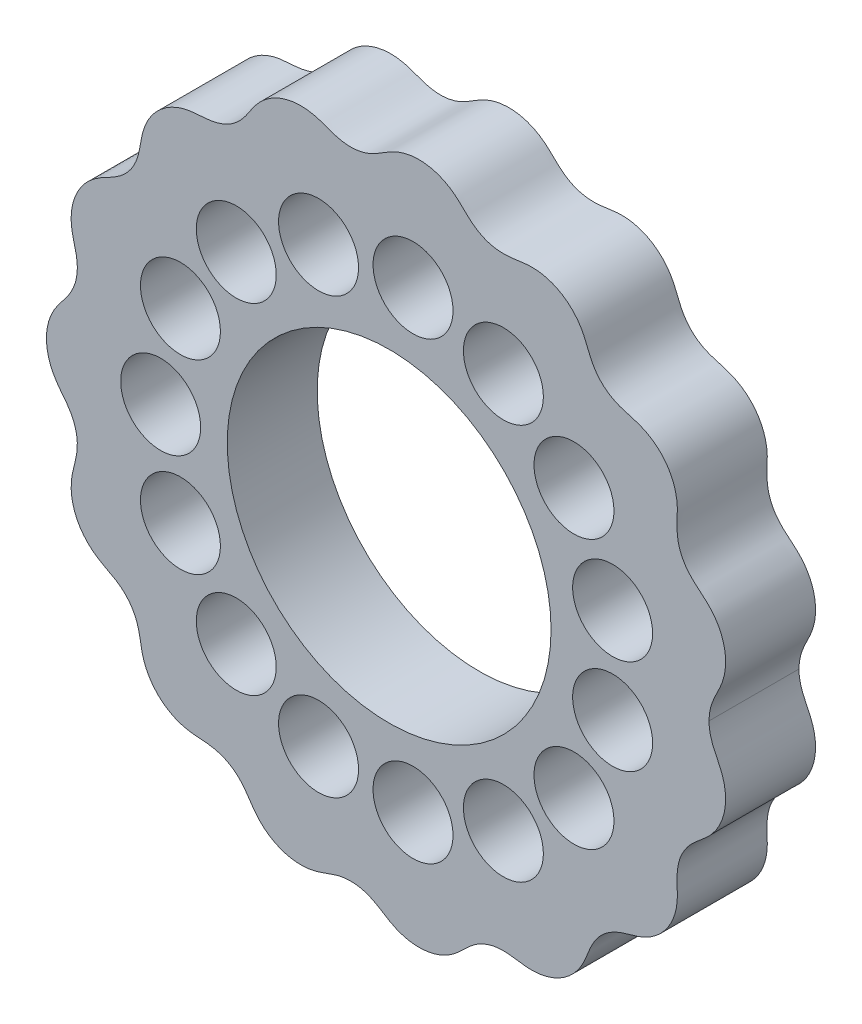
SolidWorks part; units mm, degrees
material "ABS"
ref_plane "Front Plane" through (0, 0, 0) normal (0, 0, 1) x (1, 0, 0)
ref_plane "Top Plane" through (0, 0, 0) normal (0, 1, 0) x (1, 0, 0)
ref_plane "Right Plane" through (0, 0, 0) normal (1, 0, 0) x (0, 0, -1)
sketch "Sketch2" plane through (0, 0, 0) normal (0, 0, 1) x (1, 0, 0)
  line L0 (0, 0) -> (18.3781, 0) construction
  line L1 (0, 0) -> (-12.7, 0) construction
  line L6 (0, 0) -> (-26.7529, 0) construction
  circle A0 centre (0, 0) radius 9
  circle A1 centre (-12.7, 0) radius 2.2225
  circle A10 centre (-11.602, 5.1656) radius 2.2225
  circle A11 centre (-8.498, 9.4379) radius 2.2225
  circle A12 centre (-3.9245, 12.0784) radius 2.2225
  circle A13 centre (1.3275, 12.6304) radius 2.2225
  circle A14 centre (6.35, 10.9985) radius 2.2225
  circle A15 centre (10.2745, 7.4649) radius 2.2225
  circle A16 centre (12.4225, 2.6405) radius 2.2225
  circle A17 centre (12.4225, -2.6405) radius 2.2225
  circle A18 centre (10.2745, -7.4649) radius 2.2225
  circle A19 centre (6.35, -10.9985) radius 2.2225
  circle A20 centre (1.3275, -12.6304) radius 2.2225
  circle A21 centre (-3.9245, -12.0784) radius 2.2225
  circle A22 centre (-8.498, -9.4379) radius 2.2225
  circle A23 centre (-11.602, -5.1656) radius 2.2225
  spline S0 degree 4 poles (17.78, 0) (17.78, 0.0244) (17.7807, 0.067) (17.7836, 0.1435) (17.7924, 0.267) (17.8127, 0.4353) (17.858, 0.6662) (17.9448, 0.9544) (18.081, 1.2802) (18.243, 1.6063) (18.4518, 2.028) (18.6305, 2.5252) (18.7221, 3.0926) (18.6984, 3.6926) (18.5877, 4.2118) (18.3912, 4.7145) (18.1084, 5.1856) (17.7679, 5.5735) (17.4029, 5.8854) (17.008, 6.2075) (16.5682, 6.6286) (16.2327, 7.1481) (16.0524, 7.7356) (16.0001, 8.251) (15.9991, 8.6116) (16.0206, 9.0306) (16.0292, 9.5107) (15.9471, 10.1461) (15.6638, 10.8967) (15.1871, 11.5476) (14.5569, 12.0443) (13.9761, 12.3143) (13.5161, 12.452) (13.1111, 12.5616) (12.7691, 12.6758) (12.2967, 12.8885) (11.871, 13.1931) (11.5254, 13.5862) (11.2662, 14.0347) (11.1178, 14.3634) (10.9667, 14.7548) (10.7805, 15.1975) (10.4492, 15.7456) (9.9577, 16.2466) (9.3671, 16.6208) (8.7488, 16.8381) (8.2396, 16.9232) (7.7623, 16.9292) (7.3264, 16.8812) (6.8495, 16.8026) (6.3206, 16.7557) (5.7346, 16.8115) (5.1268, 17.0239) (4.6337, 17.3466) (4.246, 17.7093) (3.9151, 18.0408) (3.6067, 18.3071) (3.1184, 18.6387) (2.4323, 18.9214) (1.6414, 19.0195) (0.8132, 18.8837) (0.2219, 18.6371) (-0.1896, 18.3896) (-0.5417, 18.1614) (-0.8545, 17.9819) (-1.327, 17.7696) (-1.9259, 17.632) (-2.5436, 17.6628) (-3.1282, 17.833) (-3.6046, 18.0141) (-4.0571, 18.1742) (-4.6853, 18.2995) (-5.492, 18.271) (-6.2641, 18.0249) (-6.9363, 17.5833) (-7.3777, 17.1156) (-7.6524, 16.7235) (-7.8817, 16.371) (-8.0964, 16.0772) (-8.4472, 15.686) (-8.8732, 15.3689) (-9.3609, 15.1585) (-9.8751, 15.0503) (-10.2369, 15.0113) (-10.6568, 14.9889) (-11.1337, 14.9471) (-11.7594, 14.7987) (-12.478, 14.4373) (-13.0772, 13.8918) (-13.5052, 13.2073) (-13.7107, 12.6007) (-13.7984, 12.1286) (-13.8654, 11.7146) (-13.9442, 11.3624) (-14.1083, 10.8715) (-14.3688, 10.4167) (-14.7255, 10.0347) (-15.2185, 9.6772) (-15.6699, 9.439) (-16.1793, 9.1821) (-16.7602, 8.7371) (-17.2688, 8.1172) (-17.5941, 7.3784) (-17.7091, 6.5847) (-17.6525, 5.9464) (-17.5418, 5.4793) (-17.4111, 4.9868) (-17.3233, 4.5098) (-17.321, 3.9878) (-17.4303, 3.4791) (-17.5906, 3.0811) (-17.7875, 2.7393) (-17.998, 2.4467) (-18.2143, 2.1781) (-18.4158, 1.9169) (-18.5901, 1.6545) (-18.7342, 1.3913) (-18.8479, 1.128) (-18.9239, 0.8973) (-18.9725, 0.705) (-19.0024, 0.553) (-19.0216, 0.4311) (-19.0342, 0.3261) (-19.042, 0.2308) (-19.0474, 0.131) (-19.0494, 0.0653) (-19.05, 0.0261) (-19.05, 0) knots 0.076308 0.076308 0.076308 0.076308 0.076308 0.077887 0.079057 0.080226 0.082566 0.087244 0.091922 0.0966 0.101861 0.107122 0.117645 0.12533 0.133015 0.139766 0.146517 0.154702 0.162887 0.167804 0.172722 0.182557 0.196068 0.200986 0.205904 0.210822 0.21574 0.223925 0.23211 0.245612 0.259114 0.267299 0.275484 0.280401 0.285319 0.290237 0.295154 0.308665 0.313583 0.318501 0.323419 0.328337 0.336522 0.344707 0.358209 0.366269 0.37433 0.380311 0.386291 0.392272 0.398253 0.406737 0.415222 0.424152 0.433082 0.438638 0.444195 0.449751 0.455308 0.470806 0.484308 0.492493 0.500678 0.505596 0.510514 0.515432 0.52035 0.533861 0.543696 0.548613 0.553531 0.561716 0.5699 0.583403 0.597169 0.605269 0.613369 0.618332 0.623295 0.628258 0.633221 0.646999 0.651962 0.656925 0.661888 0.666852 0.674952 0.683052 0.696818 0.71032 0.718505 0.726689 0.731607 0.736524 0.741442 0.746359 0.759871 0.764789 0.769707 0.779543 0.787728 0.795913 0.809415 0.822917 0.831101 0.839286 0.844204 0.849122 0.858957 0.865712 0.872468 0.877386 0.882304 0.887222 0.89214 0.896232 0.900324 0.904417 0.908509 0.911885 0.913573 0.91526 0.916948 0.918636 0.91948 0.920324 0.922011 0.922011 0.922011 0.922011 0.922011
  spline S2 degree 4 poles (18.0179, 5.2689) (18.0967, 5.1695) (18.2438, 4.9626) (18.4281, 4.6332) (18.6002, 4.1637) (18.6964, 3.6778) (18.7168, 3.1875) (18.6633, 2.7196) (18.5471, 2.2841) (18.4034, 1.9335) (18.2685, 1.6576) (18.1548, 1.4282) (18.0675, 1.2429) (17.9837, 1.0451) (17.9184, 0.8621) (17.87, 0.6956) (17.8357, 0.5462) (17.8134, 0.4263) (17.7965, 0.3075) (17.7852, 0.181) (17.7796, 0.0449) (17.7795, -0.0344) (17.7836, -0.1435) (17.7924, -0.267) (17.8127, -0.4353) (17.858, -0.6662) (17.9448, -0.9544) (18.081, -1.2802) (18.243, -1.6063) (18.4518, -2.028) (18.6305, -2.5252) (18.7221, -3.0926) (18.6984, -3.6926) (18.5877, -4.2118) (18.3912, -4.7145) (18.1084, -5.1856) (17.7679, -5.5735) (17.4029, -5.8854) (17.008, -6.2075) (16.5682, -6.6286) (16.2327, -7.1481) (16.0524, -7.7356) (16.0001, -8.251) (15.9991, -8.6116) (16.0206, -9.0306) (16.0292, -9.5107) (15.9471, -10.1461) (15.6638, -10.8967) (15.1871, -11.5476) (14.5569, -12.0443) (13.9761, -12.3143) (13.5161, -12.452) (13.1111, -12.5616) (12.7691, -12.6758) (12.2967, -12.8885) (11.871, -13.1931) (11.5254, -13.5862) (11.2662, -14.0347) (11.1178, -14.3634) (10.9667, -14.7548) (10.7805, -15.1975) (10.4492, -15.7456) (9.9577, -16.2466) (9.3671, -16.6208) (8.7488, -16.8381) (8.2396, -16.9232) (7.7623, -16.9292) (7.3264, -16.8812) (6.8495, -16.8026) (6.3206, -16.7557) (5.7346, -16.8115) (5.1268, -17.0239) (4.6337, -17.3466) (4.246, -17.7093) (3.9151, -18.0408) (3.6067, -18.3071) (3.1184, -18.6387) (2.4323, -18.9214) (1.6414, -19.0195) (0.8132, -18.8837) (0.2219, -18.6371) (-0.1896, -18.3896) (-0.5417, -18.1614) (-0.8545, -17.9819) (-1.327, -17.7696) (-1.9259, -17.632) (-2.5436, -17.6628) (-3.1282, -17.833) (-3.6046, -18.0141) (-4.0571, -18.1742) (-4.6853, -18.2995) (-5.492, -18.271) (-6.2641, -18.0249) (-6.9363, -17.5833) (-7.3777, -17.1156) (-7.6524, -16.7235) (-7.8817, -16.371) (-8.0964, -16.0772) (-8.4472, -15.686) (-8.8732, -15.3689) (-9.3609, -15.1585) (-9.8751, -15.0503) (-10.2369, -15.0113) (-10.6568, -14.9889) (-11.1337, -14.9471) (-11.7594, -14.7987) (-12.478, -14.4373) (-13.0772, -13.8918) (-13.5052, -13.2073) (-13.7107, -12.6007) (-13.7984, -12.1286) (-13.8654, -11.7146) (-13.9442, -11.3624) (-14.1083, -10.8715) (-14.3688, -10.4167) (-14.7255, -10.0347) (-15.2185, -9.6772) (-15.6699, -9.439) (-16.1793, -9.1821) (-16.7602, -8.7371) (-17.2688, -8.1172) (-17.5941, -7.3784) (-17.7091, -6.5847) (-17.6525, -5.9464) (-17.5418, -5.4793) (-17.4111, -4.9868) (-17.3233, -4.5098) (-17.321, -3.9878) (-17.4303, -3.4791) (-17.5906, -3.0811) (-17.7875, -2.7393) (-17.998, -2.4467) (-18.2143, -2.1781) (-18.4158, -1.9169) (-18.5901, -1.6545) (-18.7342, -1.3913) (-18.8479, -1.128) (-18.9239, -0.8973) (-18.9725, -0.705) (-19.0024, -0.553) (-19.0216, -0.4311) (-19.0342, -0.3261) (-19.042, -0.2308) (-19.0474, -0.131) (-19.0504, -0.0335) (-19.0504, 0.0413) (-19.0459, 0.1761) (-19.0369, 0.301) (-19.0234, 0.4176) (-19.0054, 0.5353) (-18.9774, 0.6826) (-18.941, 0.8318) (-18.8956, 0.983) (-18.8291, 1.1675) (-18.7489, 1.3556) (-18.6554, 1.5376) (-18.55, 1.7128) (-18.4483, 1.8647) (-18.3539, 1.9954) (-18.2199, 2.1704) (-17.987, 2.4608) (-17.7218, 2.82) (-17.4872, 3.2877) (-17.3418, 3.8498) (-17.317, 4.3198) (-17.3641, 4.7421) (-17.4293, 5.0391) (-17.4654, 5.1867) (-17.4841, 5.2604) knots 0 0 0 0 0 0.006928 0.013855 0.020533 0.02721 0.033888 0.040566 0.046161 0.051756 0.054554 0.057351 0.060149 0.062947 0.066287 0.067957 0.069627 0.071297 0.072967 0.074638 0.076308 0.077887 0.079057 0.080226 0.082566 0.087244 0.091922 0.0966 0.101861 0.107122 0.117645 0.12533 0.133015 0.139766 0.146517 0.154702 0.162887 0.167804 0.172722 0.182557 0.196068 0.200986 0.205904 0.210822 0.21574 0.223925 0.23211 0.245612 0.259114 0.267299 0.275484 0.280401 0.285319 0.290237 0.295154 0.308665 0.313583 0.318501 0.323419 0.328337 0.336522 0.344707 0.358209 0.366269 0.37433 0.380311 0.386291 0.392272 0.398253 0.406737 0.415222 0.424152 0.433082 0.438638 0.444195 0.449751 0.455308 0.470806 0.484308 0.492493 0.500678 0.505596 0.510514 0.515432 0.52035 0.533861 0.543696 0.548613 0.553531 0.561716 0.5699 0.583403 0.597169 0.605269 0.613369 0.618332 0.623295 0.628258 0.633221 0.646999 0.651962 0.656925 0.661888 0.666852 0.674952 0.683052 0.696818 0.71032 0.718505 0.726689 0.731607 0.736524 0.741442 0.746359 0.759871 0.764789 0.769707 0.779543 0.787728 0.795913 0.809415 0.822917 0.831101 0.839286 0.844204 0.849122 0.858957 0.865712 0.872468 0.877386 0.882304 0.887222 0.89214 0.896232 0.900324 0.904417 0.908509 0.911885 0.913573 0.91526 0.916948 0.918636 0.91948 0.920324 0.922011 0.923645 0.925278 0.926911 0.928545 0.930178 0.931811 0.935078 0.936939 0.9388 0.942522 0.946244 0.948105 0.949966 0.95251 0.955054 0.960142 0.970319 0.976856 0.983392 0.991696 0.995848 1 1 1 1 1 construction
  spline S3 degree 4 poles (17.78, 0) (17.78, -0.0244) (17.7807, -0.067) (17.7836, -0.1435) (17.7924, -0.267) (17.8127, -0.4353) (17.858, -0.6662) (17.9448, -0.9544) (18.081, -1.2802) (18.243, -1.6063) (18.4518, -2.028) (18.6305, -2.5252) (18.7221, -3.0926) (18.6984, -3.6926) (18.5877, -4.2118) (18.3912, -4.7145) (18.1084, -5.1856) (17.7679, -5.5735) (17.4029, -5.8854) (17.008, -6.2075) (16.5682, -6.6286) (16.2327, -7.1481) (16.0524, -7.7356) (16.0001, -8.251) (15.9991, -8.6116) (16.0206, -9.0306) (16.0292, -9.5107) (15.9471, -10.1461) (15.6638, -10.8967) (15.1871, -11.5476) (14.5569, -12.0443) (13.9761, -12.3143) (13.5161, -12.452) (13.1111, -12.5616) (12.7691, -12.6758) (12.2967, -12.8885) (11.871, -13.1931) (11.5254, -13.5862) (11.2662, -14.0347) (11.1178, -14.3634) (10.9667, -14.7548) (10.7805, -15.1975) (10.4492, -15.7456) (9.9577, -16.2466) (9.3671, -16.6208) (8.7488, -16.8381) (8.2396, -16.9232) (7.7623, -16.9292) (7.3264, -16.8812) (6.8495, -16.8026) (6.3206, -16.7557) (5.7346, -16.8115) (5.1268, -17.0239) (4.6337, -17.3466) (4.246, -17.7093) (3.9151, -18.0408) (3.6067, -18.3071) (3.1184, -18.6387) (2.4323, -18.9214) (1.6414, -19.0195) (0.8132, -18.8837) (0.2219, -18.6371) (-0.1896, -18.3896) (-0.5417, -18.1614) (-0.8545, -17.9819) (-1.327, -17.7696) (-1.9259, -17.632) (-2.5436, -17.6628) (-3.1282, -17.833) (-3.6046, -18.0141) (-4.0571, -18.1742) (-4.6853, -18.2995) (-5.492, -18.271) (-6.2641, -18.0249) (-6.9363, -17.5833) (-7.3777, -17.1156) (-7.6524, -16.7235) (-7.8817, -16.371) (-8.0964, -16.0772) (-8.4472, -15.686) (-8.8732, -15.3689) (-9.3609, -15.1585) (-9.8751, -15.0503) (-10.2369, -15.0113) (-10.6568, -14.9889) (-11.1337, -14.9471) (-11.7594, -14.7987) (-12.478, -14.4373) (-13.0772, -13.8918) (-13.5052, -13.2073) (-13.7107, -12.6007) (-13.7984, -12.1286) (-13.8654, -11.7146) (-13.9442, -11.3624) (-14.1083, -10.8715) (-14.3688, -10.4167) (-14.7255, -10.0347) (-15.2185, -9.6772) (-15.6699, -9.439) (-16.1793, -9.1821) (-16.7602, -8.7371) (-17.2688, -8.1172) (-17.5941, -7.3784) (-17.7091, -6.5847) (-17.6525, -5.9464) (-17.5418, -5.4793) (-17.4111, -4.9868) (-17.3233, -4.5098) (-17.321, -3.9878) (-17.4303, -3.4791) (-17.5906, -3.0811) (-17.7875, -2.7393) (-17.998, -2.4467) (-18.2143, -2.1781) (-18.4158, -1.9169) (-18.5901, -1.6545) (-18.7342, -1.3913) (-18.8479, -1.128) (-18.9239, -0.8973) (-18.9725, -0.705) (-19.0024, -0.553) (-19.0216, -0.4311) (-19.0342, -0.3261) (-19.042, -0.2308) (-19.0474, -0.131) (-19.0494, -0.0653) (-19.05, -0.0261) (-19.05, 0) knots 0.076308 0.076308 0.076308 0.076308 0.076308 0.077887 0.079057 0.080226 0.082566 0.087244 0.091922 0.0966 0.101861 0.107122 0.117645 0.12533 0.133015 0.139766 0.146517 0.154702 0.162887 0.167804 0.172722 0.182557 0.196068 0.200986 0.205904 0.210822 0.21574 0.223925 0.23211 0.245612 0.259114 0.267299 0.275484 0.280401 0.285319 0.290237 0.295154 0.308665 0.313583 0.318501 0.323419 0.328337 0.336522 0.344707 0.358209 0.366269 0.37433 0.380311 0.386291 0.392272 0.398253 0.406737 0.415222 0.424152 0.433082 0.438638 0.444195 0.449751 0.455308 0.470806 0.484308 0.492493 0.500678 0.505596 0.510514 0.515432 0.52035 0.533861 0.543696 0.548613 0.553531 0.561716 0.5699 0.583403 0.597169 0.605269 0.613369 0.618332 0.623295 0.628258 0.633221 0.646999 0.651962 0.656925 0.661888 0.666852 0.674952 0.683052 0.696818 0.71032 0.718505 0.726689 0.731607 0.736524 0.741442 0.746359 0.759871 0.764789 0.769707 0.779543 0.787728 0.795913 0.809415 0.822917 0.831101 0.839286 0.844204 0.849122 0.858957 0.865712 0.872468 0.877386 0.882304 0.887222 0.89214 0.896232 0.900324 0.904417 0.908509 0.911885 0.913573 0.91526 0.916948 0.918636 0.91948 0.920324 0.922011 0.922011 0.922011 0.922011 0.922011
  dimension "D1" = 18
  dimension "D2" = 4.445
  dimension "D3" = 12.7
  dimension "D4" = 15
  dimension "D5" = 12.7
extrude "Boss-Extrude1" add sketch "Sketch2" along normal blind 5
